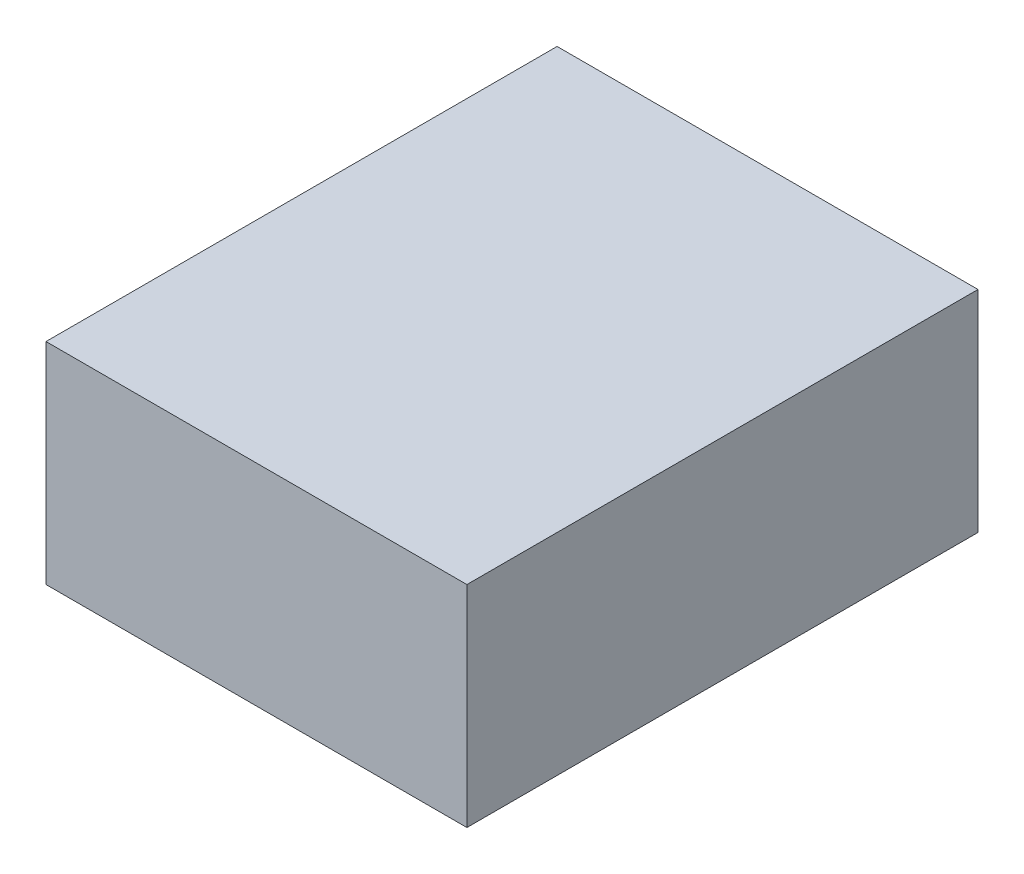
SolidWorks part; units mm, degrees
material "Polyethylene Cross-Linked"
ref_plane "Front Plane" through (0, 0, 0) normal (0, 0, 1) x (1, 0, 0)
ref_plane "Top Plane" through (0, 0, 0) normal (0, 1, 0) x (1, 0, 0)
ref_plane "Right Plane" through (0, 0, 0) normal (1, 0, 0) x (0, 0, -1)
sketch "Sketch1" plane through (0, 0, 0) normal (0, 1, 0) x (1, 0, 0)
  line L1 (-177.8, 215.9) -> (177.8, 215.9)
  line L2 (-177.8, 215.9) -> (-177.8, -215.9)
  line L3 (-177.8, -215.9) -> (177.8, -215.9)
  line L4 (177.8, 215.9) -> (177.8, -215.9)
  line L5 (-177.8, 215.9) -> (177.8, -215.9) construction
  line L6 (-177.8, -215.9) -> (177.8, 215.9) construction
  point P0 (0, 0)
  dimension "D1" = 355.6
  dimension "D2" = 431.8
extrude "Boss-Extrude1" add sketch "Sketch1" along normal blind 177.8
